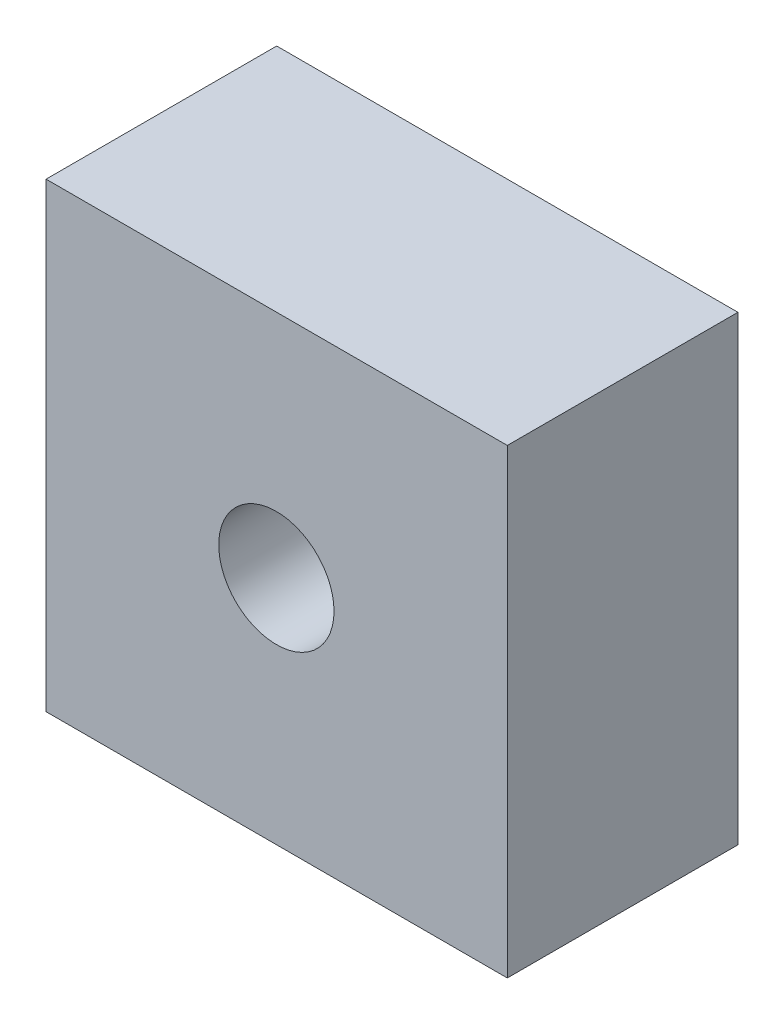
SolidWorks part; units mm, degrees
ref_plane "前视基准面" through (0, 0, 0) normal (0, 0, 1) x (1, 0, 0)
ref_plane "上视基准面" through (0, 0, 0) normal (0, 1, 0) x (1, 0, 0)
ref_plane "右视基准面" through (0, 0, 0) normal (1, 0, 0) x (0, 0, -1)
other "Configuration Table"
sketch "草图1" plane through (0, 0, 0) normal (0, 0, 1) x (1, 0, 0)
  line L1 (0, 0) -> (20, 0)
  line L2 (0, 0) -> (0, 20)
  line L3 (0, 20) -> (20, 20)
  line L4 (20, 0) -> (20, 20)
extrude "BaseBox" add sketch "草图1" along normal blind 10
hole_wizard "孔1" positions "草图3" profile "草图2" legacy
sketch "草图3" plane through (0, 0, 10) normal (0, 0, 1) x (1, 0, 0)
  point P0 (9.9865, 10.0143)
sketch "草图2" plane through (9.9865, 10.0143, 10) normal (1, 0, 0) x (0, -1, 0)
  line L0 (0, 0) -> (0, 5)
  line L1 (0, 5) -> (2.5, 5)
  line L2 (2.5, 5) -> (2.5, 0)
  line L3 (2.5, 0) -> (0, 0)
  line L4 (0, 110) -> (0, -10) construction
  dimension "直径" = 5
  dimension "深度" = 5
